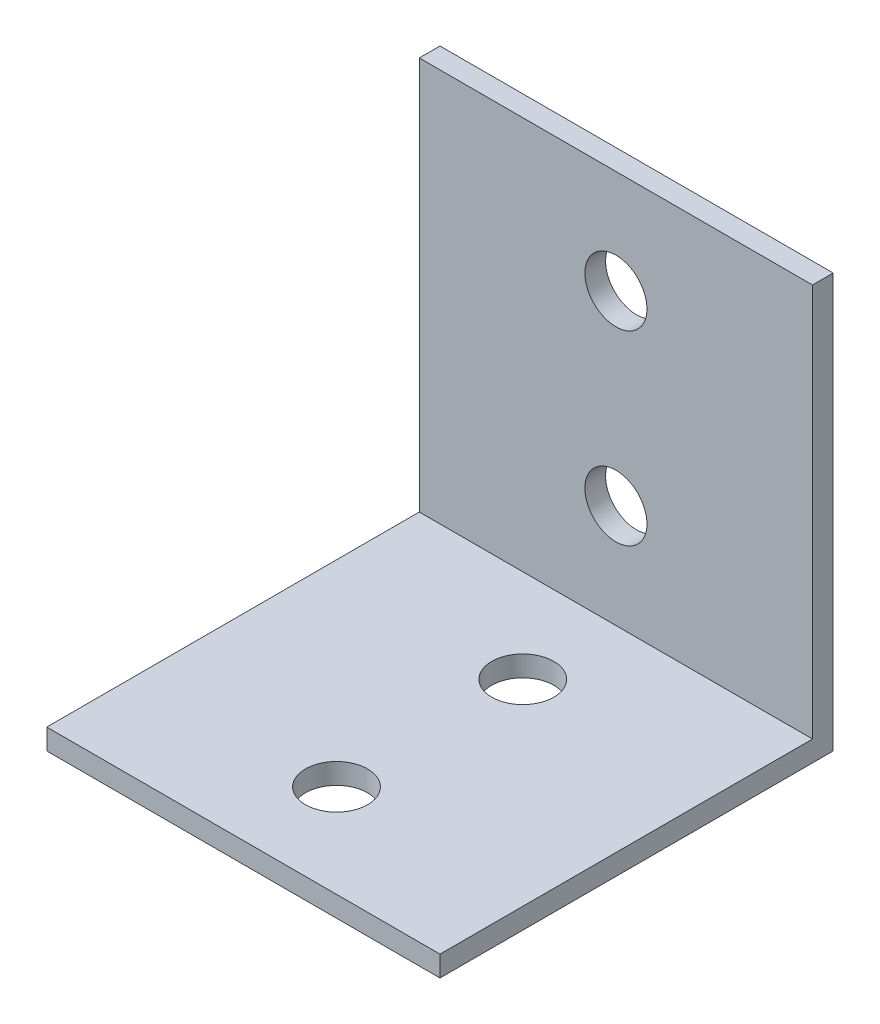
SolidWorks part; units mm, degrees
ref_plane "Front Plane" through (0, 0, 0) normal (0, 0, 1) x (1, 0, 0)
ref_plane "Top Plane" through (0, 0, 0) normal (0, 1, 0) x (1, 0, 0)
ref_plane "Right Plane" through (0, 0, 0) normal (1, 0, 0) x (0, 0, -1)
sketch "Sketch1" plane through (0, 0, 0) normal (0, 1, 0) x (1, 0, 0)
  line L1 (-32.0817, 34.7382) -> (5.9183, 34.7382)
  line L2 (-32.0817, 34.7382) -> (-32.0817, -3.2618)
  line L3 (-32.0817, -3.2618) -> (5.9183, -3.2618)
  line L4 (5.9183, 34.7382) -> (5.9183, -3.2618)
  dimension "D1" = 38
  dimension "D2" = 38
extrude "Boss-Extrude1" add sketch "Sketch1" along normal blind 2
sketch "Sketch2" plane through (0, 2, 0) normal (0, 1, 0) x (1, 0, 0)
  line L1 (-32.0817, 34.7382) -> (5.9183, 34.7382)
  line L2 (-32.0817, 34.7382) -> (-32.0817, 32.7382)
  line L3 (-32.0817, 32.7382) -> (5.9183, 32.7382)
  line L4 (5.9183, 34.7382) -> (5.9183, 32.7382)
  dimension "D1" = 2
  dimension "D2" = 38
extrude "Boss-Extrude2" add sketch "Sketch2" along normal blind 38
sketch "Sketch3" plane through (0, 0, -32.7382) normal (0, 0, 1) x (1, 0, 0)
  line L0 (-32.0817, 21) -> (5.9183, 21) construction
  line L1 (-32.0817, 40) -> (-32.0817, 2) construction
  line L2 (5.9183, 40) -> (5.9183, 2) construction
  line L3 (-13.0817, 40) -> (-13.0817, 2) construction
  line L4 (-32.0817, 40) -> (5.9183, 40) construction
  line L5 (-32.0817, 2) -> (5.9183, 2) construction
  circle A0 centre (-13.0817, 30) radius 3
  circle A1 centre (-13.0817, 12) radius 3
  dimension "D1" = 6
  dimension "D2" = 9
extrude "Cut-Extrude1" cut sketch "Sketch3" against normal blind 10
sketch "Sketch4" plane through (0, 2, 0) normal (0, 1, 0) x (1, 0, 0)
  line L0 (-32.0817, 14.7382) -> (5.9183, 14.7382) construction
  line L1 (-32.0817, 32.7382) -> (-32.0817, -3.2618) construction
  line L2 (5.9183, -3.2618) -> (5.9183, 32.7382) construction
  line L3 (-13.0817, 32.7382) -> (-13.0817, -3.2618) construction
  line L4 (-32.0817, 32.7382) -> (5.9183, 32.7382) construction
  line L5 (-32.0817, -3.2618) -> (5.9183, -3.2618) construction
  circle A0 centre (-13.0817, 5.7382) radius 3
  circle A1 centre (-13.0817, 23.7382) radius 3
  point P14 (-13.0817, 4.9926)
  dimension "D1" = 6
  dimension "D2" = 9
extrude "Cut-Extrude2" cut sketch "Sketch4" against normal blind 10
